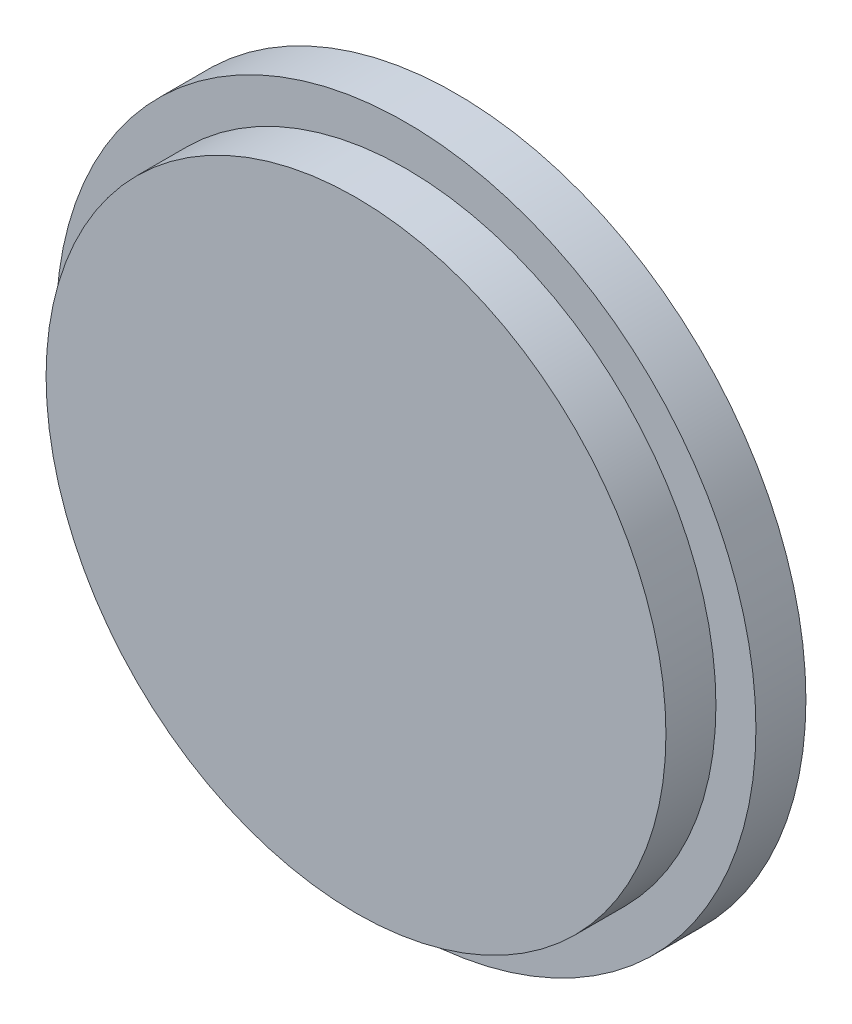
SolidWorks part; units mm, degrees
ref_plane "Front Plane" through (0, 0, 0) normal (0, 0, 1) x (1, 0, 0)
ref_plane "Top Plane" through (0, 0, 0) normal (0, 1, 0) x (1, 0, 0)
ref_plane "Right Plane" through (0, 0, 0) normal (1, 0, 0) x (0, 0, -1)
sketch "Sketch1" plane through (0, 0, 0) normal (0, 0, 1) x (1, 0, 0)
  circle A0 centre (0, 0) radius 35
  dimension "D1" = 70
extrude "Boss-Extrude1" add sketch "Sketch1" along normal blind 5
sketch "Sketch2" plane through (0, 0, 5) normal (0, 0, 1) x (1, 0, 0)
  circle A0 centre (0, 0) radius 31
  dimension "D1" = 62
extrude "Boss-Extrude2" add sketch "Sketch2" along normal blind 5
